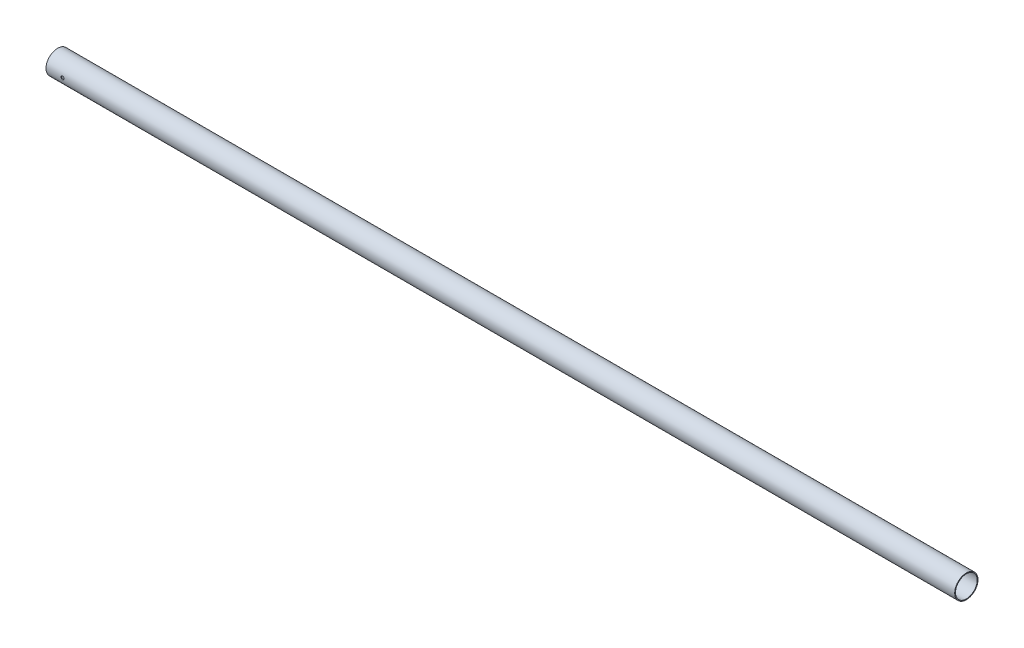
SolidWorks part; units mm, degrees
ref_plane "Front Plane" through (0, 0, 0) normal (0, 0, 1) x (1, 0, 0)
ref_plane "Top Plane" through (0, 0, 0) normal (0, 1, 0) x (1, 0, 0)
ref_plane "Right Plane" through (0, 0, 0) normal (1, 0, 0) x (0, 0, -1)
sketch "Sketch1" plane through (0, 0, 0) normal (1, 0, 0) x (0, 0, -1)
  circle A0 centre (0, 0) radius 12.7
  circle A1 centre (0, 0) radius 11.811
extrude "Boss-Extrude1" add sketch "Sketch1" along normal blind 991.014
sketch "Sketch2" plane through (0, 0, 0) normal (0, 0, 1) x (1, 0, 0)
  circle A0 centre (18, 0) radius 1.7
extrude "Cut-Extrude1" cut sketch "Sketch2" against normal through all and the other way through all
